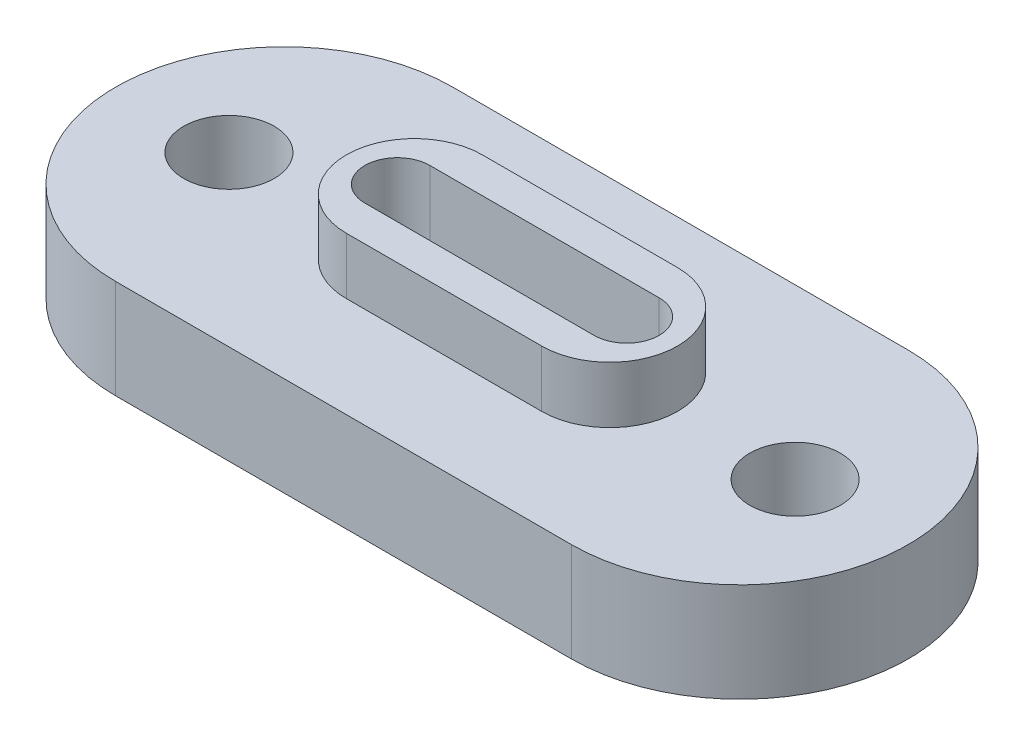
SolidWorks part; units mm, degrees
ref_plane "Front Plane" through (0, 0, 0) normal (0, 0, 1) x (1, 0, 0)
ref_plane "Top Plane" through (0, 0, 0) normal (0, 1, 0) x (1, 0, 0)
ref_plane "Right Plane" through (0, 0, 0) normal (1, 0, 0) x (0, 0, -1)
sketch "Sketch1" plane through (0, 0, 0) normal (0, 1, 0) x (1, 0, 0)
  line L0 (-3.45, 0) -> (3.45, 0) construction
  line L1 (-3.45, 2.4) -> (3.45, 2.4)
  line L2 (-3.45, -2.4) -> (3.45, -2.4)
  line L3 (-4.05, 0) -> (4.05, 0) construction
  line L4 (-4.05, 1.15) -> (4.05, 1.15)
  line L5 (-4.05, -1.15) -> (4.05, -1.15)
  arc A0 (-3.45, 2.4) -> (-3.45, -2.4) centre (-3.45, 0) ccw
  arc A1 (3.45, -2.4) -> (3.45, 2.4) centre (3.45, 0) ccw
  arc A2 (-4.05, 1.15) -> (-4.05, -1.15) centre (-4.05, 0) ccw
  arc A3 (4.05, -1.15) -> (4.05, 1.15) centre (4.05, 0) ccw
  point P2 (0, 0)
  point P10 (0, 0)
extrude "Boss-Extrude1" add sketch "Sketch1" along normal blind 2
sketch "Sketch2" plane through (0, 0, 0) normal (0, -1, 0) x (1, 0, 0)
  line L0 (0, -2.5) -> (0, 2.5) construction
  line L1 (-5.95, -2.5) -> (-5.95, 2.5) construction
  line L2 (5.95, -2.5) -> (5.95, 2.5) construction
  line L3 (4.05, 0) -> (-4.05, 0) construction
  line L4 (4.05, -1.15) -> (-4.05, -1.15)
  line L5 (4.05, 1.15) -> (-4.05, 1.15)
  line L6 (-8.05, 0) -> (8.05, 0) construction
  line L7 (-8.05, 5.95) -> (8.05, 5.95)
  line L8 (-8.05, -5.95) -> (8.05, -5.95)
  arc A0 (-5.95, -2.5) -> (5.95, -2.5) centre (0, -2.5) ccw construction
  arc A1 (5.95, 2.5) -> (-5.95, 2.5) centre (0, 2.5) ccw construction
  arc A2 (4.05, -1.15) -> (4.05, 1.15) centre (4.05, 0) ccw
  arc A3 (-4.05, 1.15) -> (-4.05, -1.15) centre (-4.05, 0) ccw
  circle A4 centre (0, -5) radius 1.6 construction
  circle A5 centre (0, 5) radius 1.6 construction
  arc A6 (-8.05, 5.95) -> (-8.05, -5.95) centre (-8.05, 0) ccw
  arc A7 (8.05, -5.95) -> (8.05, 5.95) centre (8.05, 0) ccw
  circle A8 centre (-10, 0) radius 1.6
  circle A9 centre (10, 0) radius 1.6
  point P2 (0, 0)
  point P10 (0, 0)
  point P20 (0, 0)
extrude "Boss-Extrude2" add sketch "Sketch2" along normal blind 3.5
